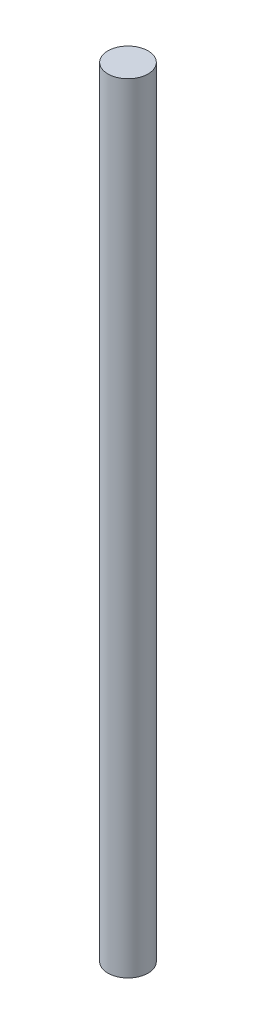
SolidWorks part; units mm, degrees
ref_plane "Front Plane" through (0, 0, 0) normal (0, 0, 1) x (1, 0, 0)
ref_plane "Top Plane" through (0, 0, 0) normal (0, 1, 0) x (1, 0, 0)
ref_plane "Right Plane" through (0, 0, 0) normal (1, 0, 0) x (0, 0, -1)
sketch "Sketch1" plane through (0, 0, 0) normal (0, 1, 0) x (1, 0, 0)
  circle A0 centre (0, 0) radius 6.75
  dimension "D1" = 13.5
extrude "Boss-Extrude1" add sketch "Sketch1" along normal blind 262
